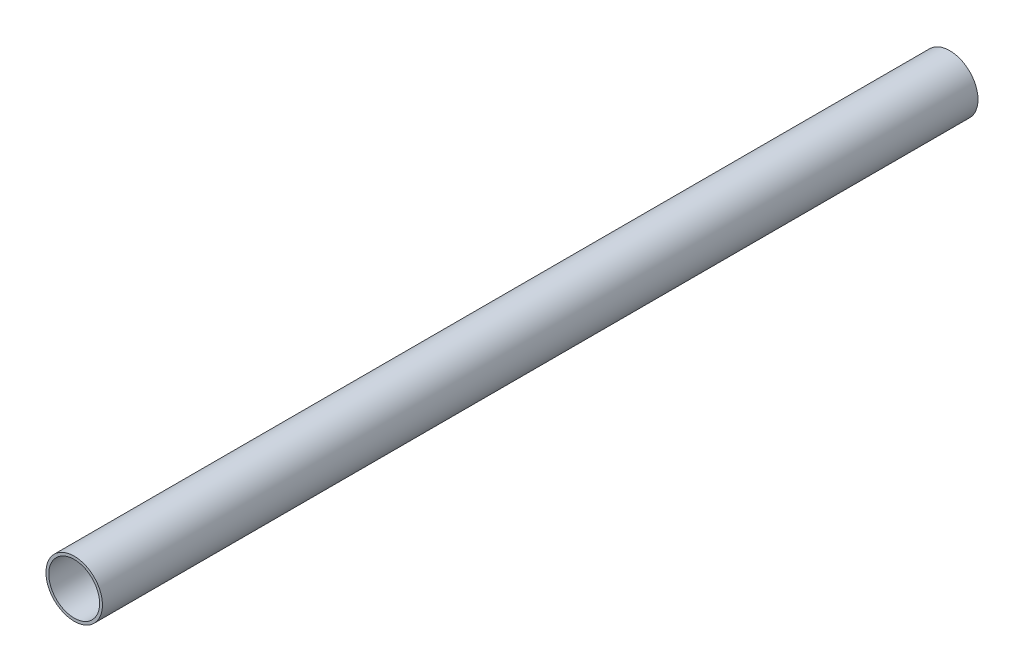
SolidWorks part; units mm, degrees
material "Thornel Mat VMA"
ref_plane "前视基准面" through (0, 0, 0) normal (0, 0, 1) x (1, 0, 0)
ref_plane "上视基准面" through (0, 0, 0) normal (0, 1, 0) x (1, 0, 0)
ref_plane "右视基准面" through (0, 0, 0) normal (1, 0, 0) x (0, 0, -1)
sketch "草图1" plane through (0, 0, 0) normal (0, 0, 1) x (1, 0, 0)
  circle A0 centre (0, 0) radius 9
  circle A1 centre (0, 0) radius 10
  dimension "D1" = 20
  dimension "D2" = 1
extrude "凸台-拉伸1" add sketch "草图1" along normal mid plane 310
